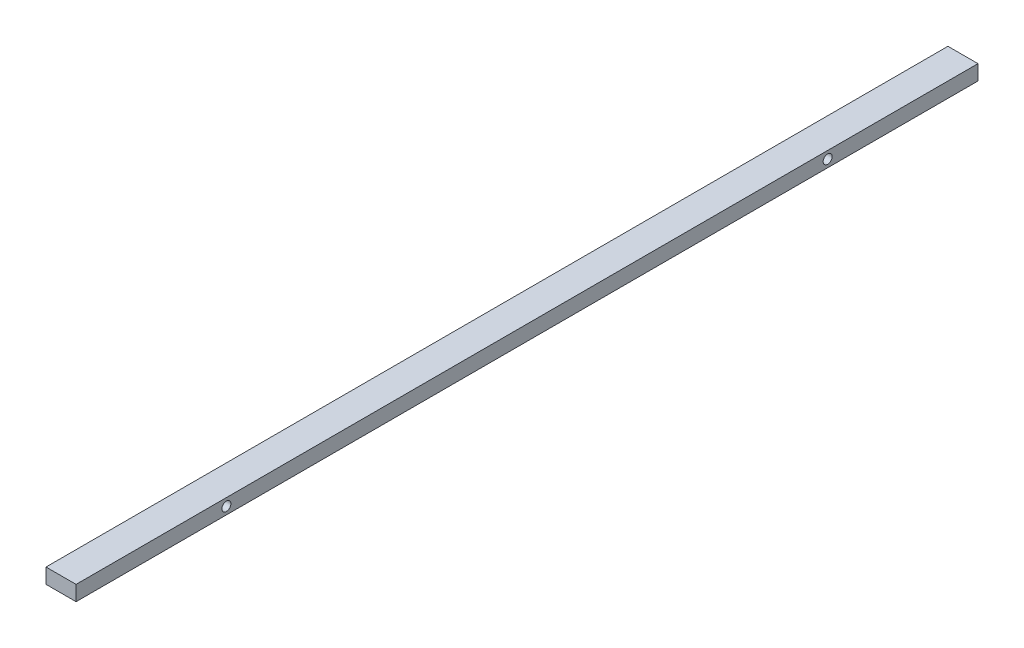
SolidWorks part; units mm, degrees
ref_plane "Front Plane" through (0, 0, 0) normal (0, 0, 1) x (1, 0, 0)
ref_plane "Top Plane" through (0, 0, 0) normal (0, 1, 0) x (1, 0, 0)
ref_plane "Right Plane" through (0, 0, 0) normal (1, 0, 0) x (0, 0, -1)
sketch "Sketch1" plane through (0, 0, 0) normal (0, 0, 1) x (1, 0, 0)
  line L1 (-4.7679, 0.3797) -> (5.2321, 0.3797)
  line L2 (-4.7679, 0.3797) -> (-4.7679, -4.6203)
  line L3 (-4.7679, -4.6203) -> (5.2321, -4.6203)
  line L4 (5.2321, 0.3797) -> (5.2321, -4.6203)
  dimension "D1" = 10
  dimension "D2" = 5
extrude "Boss-Extrude1" add sketch "Sketch1" along normal blind 300
sketch "Sketch2" plane through (0, 0.3797, 0) normal (0, 1, 0) x (1, 0, 0)
  line L0 (0, 0) -> (0, -50)
  line L1 (0.2321, -300) -> (0.2321, -250)
  line L2 (5.2321, -300) -> (-4.7679, -300) construction
  circle A0 centre (0.2321, -250) radius 1.5
  circle A1 centre (0, -50) radius 1.5
  dimension "D3" = 3
  dimension "D4" = 3
  dimension "D1" = 50
  dimension "D2" = 50
sketch "Sketch3" plane through (-4.7679, 0, 0) normal (-1, 0, 0) x (0, 0, 1)
  line L0 (0, -2.1203) -> (50, -2.1203)
  line L1 (0, 0.3797) -> (0, -4.6203) construction
  line L2 (300, -2.1203) -> (250, -2.1203)
  line L3 (300, 0.3797) -> (300, -4.6203) construction
  circle A0 centre (250, -2.1203) radius 1.5
  circle A1 centre (50, -2.1203) radius 1.5
  dimension "D2" = 3
  dimension "D4" = 3
  dimension "D1" = 50
  dimension "D3" = 50
extrude "Cut-Extrude2" cut sketch "Sketch3" against normal through all both and the other way through all
